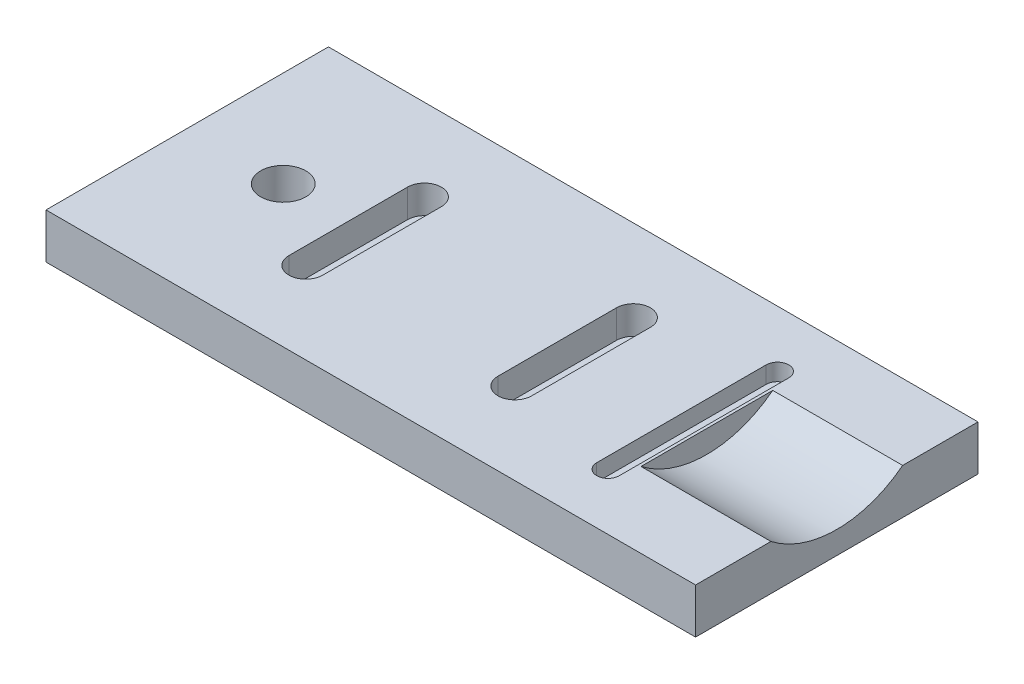
SolidWorks part; units mm, degrees
material "1060 Alloy"
ref_plane "Front Plane" through (0, 0, 0) normal (0, 0, 1) x (1, 0, 0)
ref_plane "Top Plane" through (0, 0, 0) normal (0, 1, 0) x (1, 0, 0)
ref_plane "Right Plane" through (0, 0, 0) normal (1, 0, 0) x (0, 0, -1)
sketch "Sketch1" plane through (0, 0, 0) normal (0, 1, 0) x (1, 0, 0)
  line L1 (-57.5, -25) -> (57.5, -25)
  line L2 (-57.5, -25) -> (-57.5, 25)
  line L3 (-57.5, 25) -> (57.5, 25)
  line L4 (57.5, -25) -> (57.5, 25)
  line L5 (-57.5, -25) -> (57.5, 25) construction
  line L6 (-57.5, 25) -> (57.5, -25) construction
  point P0 (0, 0)
  dimension "D1" = 115
  dimension "D2" = 50
extrude "Boss-Extrude1" add sketch "Sketch1" along normal blind 8
sketch "Sketch2" plane through (0, 8, 0) normal (0, 1, 0) x (1, 0, 0)
  line L0 (-44.2539, 0) -> (44.2539, 0) construction
  line L1 (-57.5, 25) -> (-57.5, -25) construction
  circle A0 centre (-40.5, 0) radius 4
  dimension "D1" = 8
  dimension "D2" = 17
extrude "Cut-Extrude1" cut sketch "Sketch2" against normal blind 10
sketch "Sketch3" plane through (0, 8, 0) normal (0, 1, 0) x (1, 0, 0)
  line L0 (-44.2539, 0) -> (44.2539, 0) construction
  line L2 (-29, -10.5) -> (-29, 10.5)
  line L4 (-23, -10.5) -> (-23, 10.5)
  line L5 (-29, -10.5) -> (-23, 10.5) construction
  line L6 (-29, 10.5) -> (-23, -10.5) construction
  line L7 (-57.5, 25) -> (-57.5, -25) construction
  arc A0 (-29, 10.5) -> (-23, 10.5) centre (-26, 10.5) cw
  arc A1 (-29, -10.5) -> (-23, -10.5) centre (-26, -10.5) ccw
  point P0 (-26, 0)
  dimension "D1" = 6
  dimension "D2" = 21
  dimension "D3" = 28.5
extrude "Cut-Extrude2" cut sketch "Sketch3" against normal blind 5
pattern_linear "LPattern1" count 2 spacing 37 along (1, 0, 0) of "Cut-Extrude2"
sketch "Sketch4" plane through (0, 8, 0) normal (0, 1, 0) x (1, 0, 0)
  line L0 (32, 15) -> (32, -15) construction
  line L1 (-44.2539, 0) -> (44.2539, 0) construction
  line L2 (34, 15) -> (34, -15)
  line L3 (30, 15) -> (30, -15)
  arc A0 (34, 15) -> (30, 15) centre (32, 15) ccw
  arc A1 (30, -15) -> (34, -15) centre (32, -15) ccw
  arc A2 (8, -10.5) -> (14, -10.5) centre (11, -10.5) ccw construction
  point P4 (32, 0)
  point P12 (11, -13.5)
  dimension "D1" = 4
  dimension "D2" = 30
  dimension "D3" = 21
extrude "Cut-Extrude3" cut sketch "Sketch4" against normal blind 3
sketch "Sketch5" plane through (57.5, 0, 0) normal (1, 0, 0) x (0, 0, -1)
  line L0 (0, 44.2539) -> (0, -44.2539) construction
  line L1 (-25, 8) -> (25, 8) construction
  line L2 (11.6619, 8) -> (0, 23)
  line L3 (0, 23) -> (-11.6619, 8)
  arc A0 (-11.6619, 8) -> (11.6619, 8) centre (0, 23) ccw
  dimension "D1" = 19
  dimension "D2" = 15
extrude "Cut-Extrude4" cut sketch "Sketch5" against normal blind 23
ref_plane "Plane1" through (-7.5, 0, 0) normal (-1, 0, 0) x (0, 0, 1)
sketch "Sketch9" plane through (0, 0, 0) normal (0, -1, 0) x (1, 0, 0)
  line L0 (-7.5, 24.9764) -> (-7.5, -24.9764) construction
  line L1 (-8.7874, 3.25) -> (-6.2126, 3.25)
  line L2 (-10.75, 1.2874) -> (-10.75, -1.2874)
  line L3 (-8.7874, -3.25) -> (-6.2126, -3.25)
  line L4 (-4.25, 1.2874) -> (-4.25, -1.2874)
  line L5 (-10.4268, 2.9268) -> (-4.5732, -2.9268) construction
  line L6 (-10.4268, -2.9268) -> (-4.5732, 2.9268) construction
  line L7 (44.2539, 0) -> (-44.2539, 0) construction
  arc A0 (-8.7874, 3.25) -> (-10.75, 1.2874) centre (-9.3661, 1.8661) ccw
  arc A1 (-4.25, 1.2874) -> (-6.2126, 3.25) centre (-5.6339, 1.8661) ccw
  arc A2 (-10.75, -1.2874) -> (-8.7874, -3.25) centre (-9.3661, -1.8661) ccw
  arc A3 (-6.2126, -3.25) -> (-4.25, -1.2874) centre (-5.6339, -1.8661) ccw
  point P0 (-7.5, 0)
  point P17 (-7.5, -3.25)
  point P22 (-10.75, 0)
  dimension "D2" = 3
  dimension "D3" = 1.5
  dimension "D1" = 6.5
  dimension "D4" = 6.5
extrude "Cut-Extrude8" cut sketch "Sketch9" against normal blind 5
sketch "Sketch10" plane through (0, 0, 0) normal (0, -1, 0) x (1, 0, 0)
  line L0 (-7.5, 24.9764) -> (-7.5, -24.9764) construction
  line L1 (44.2539, 0) -> (-44.2539, 0) construction
  arc A0 (-7.5, -12) -> (0.9853, 8.4853) centre (-7.5, 0) cw construction
  arc A1 (2.3995, 9.8995) -> (-7.5, -14) centre (-7.5, 0) ccw
  arc A2 (-0.4289, 7.0711) -> (-7.5, -10) centre (-7.5, 0) ccw
  arc A3 (-0.4289, 7.0711) -> (2.3995, 9.8995) centre (0.9853, 8.4853) ccw
  arc A4 (-7.5, -14) -> (-7.5, -10) centre (-7.5, -12) ccw
  point P7 (-18.5866, 4.5922)
  dimension "D3" = 12
  dimension "D1" = 4
  dimension "D2" = 225
extrude "Cut-Extrude9" cut sketch "Sketch10" against normal blind 5
